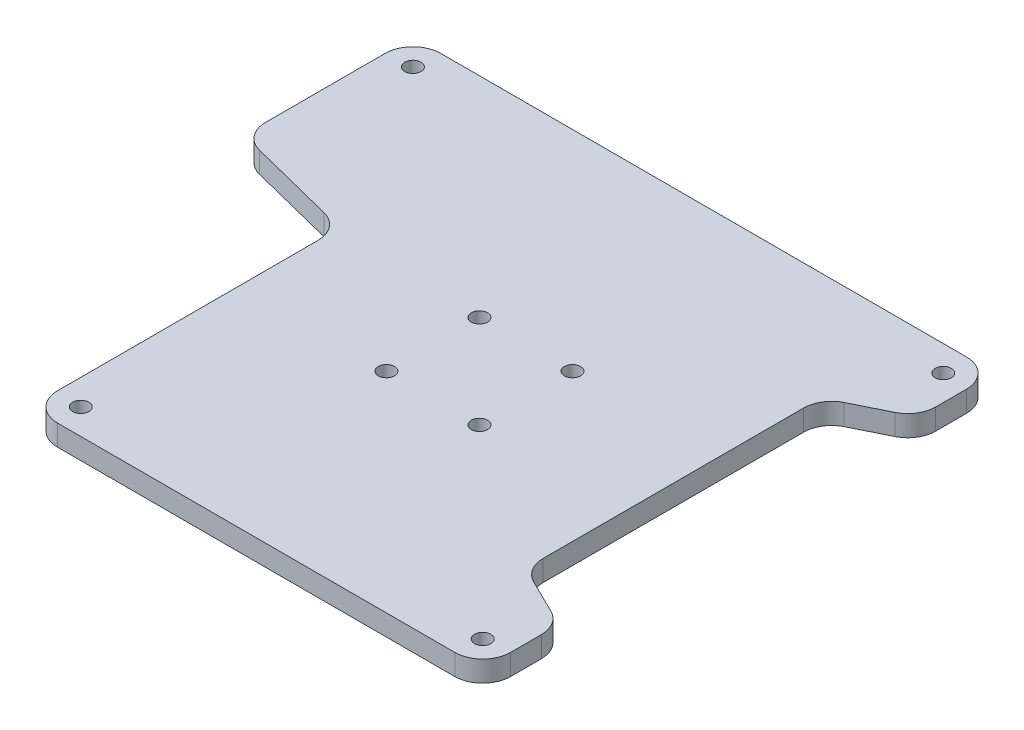
SolidWorks part; units mm, degrees
ref_plane "Front Plane" through (0, 0, 0) normal (0, 0, 1) x (1, 0, 0)
ref_plane "Top Plane" through (0, 0, 0) normal (0, 1, 0) x (1, 0, 0)
ref_plane "Right Plane" through (0, 0, 0) normal (1, 0, 0) x (0, 0, -1)
sketch "Sketch1" plane through (0, 0, 0) normal (0, 1, 0) x (1, 0, 0)
  line L0 (-41.7, 0) -> (41.7, 0) construction
  line L1 (-35.7, -55) -> (49.7, -55)
  line L2 (55.7, -49) -> (55.7, -42.3778)
  line L3 (52.3607, -37) -> (45.0393, -33.3778)
  line L4 (41.7, -28) -> (41.7, 28)
  line L5 (45.0393, 33.3778) -> (52.3607, 37)
  line L6 (55.7, 42.3778) -> (55.7, 49)
  line L7 (49.7, 55) -> (-63.3, 55)
  line L8 (-69.3, 49) -> (-69.3, 23.3173)
  line L9 (-64.7694, 17.5) -> (-46.2306, 12.8173)
  line L10 (-41.7, 7) -> (-41.7, -49)
  line L11 (-36.8, 20.5) -> (23.2, 20.5) construction
  line L12 (34.04, -3.15) -> (35.74, -3.15) construction
  line L13 (34.04, -3.15) -> (34.04, 3.15) construction
  line L14 (34.04, 3.15) -> (35.74, 3.15) construction
  line L15 (35.74, -3.15) -> (35.74, 3.15) construction
  line L16 (34.04, -3.15) -> (35.74, 3.15) construction
  line L17 (34.04, 3.15) -> (35.74, -3.15) construction
  line L18 (-33.5, -3.15) -> (-31.8, -3.15) construction
  line L19 (-33.5, -3.15) -> (-33.5, 3.15) construction
  line L20 (-33.5, 3.15) -> (-31.8, 3.15) construction
  line L21 (-31.8, -3.15) -> (-31.8, 3.15) construction
  line L22 (-33.5, -3.15) -> (-31.8, 3.15) construction
  line L23 (-33.5, 3.15) -> (-31.8, -3.15) construction
  line L24 (23.2, 20.5) -> (41.7, 20.5) construction
  line L25 (-41.7, -20) -> (-6.7, -20) construction
  line L26 (-6.7, -20) -> (-6.7, -55) construction
  line L27 (50.2, 55) -> (50.2, 49.5) construction
  line L28 (50.2, 49.5) -> (55.7, 49.5) construction
  line L29 (-63.8, 55) -> (-63.8, 49.5) construction
  line L30 (-63.8, 49.5) -> (-69.3, 49.5) construction
  line L31 (-41.7, -49.5) -> (-36.2, -49.5) construction
  line L32 (-36.2, -49.5) -> (-36.2, -55) construction
  line L33 (50.2, -55) -> (50.2, -49.5) construction
  line L34 (50.2, -49.5) -> (55.7, -49.5) construction
  line L36 (-10, -10) -> (10, -10) construction
  line L37 (-10, -10) -> (-10, 10) construction
  line L38 (-10, 10) -> (10, 10) construction
  line L39 (10, -10) -> (10, 10) construction
  line L40 (-10, -10) -> (10, 10) construction
  line L41 (-10, 10) -> (10, -10) construction
  arc A0 (49.7, -55) -> (55.7, -49) centre (49.7, -49) ccw
  arc A1 (55.7, -42.3778) -> (52.3607, -37) centre (49.7, -42.3778) ccw
  arc A2 (45.0393, -33.3778) -> (41.7, -28) centre (47.7, -28) cw
  arc A3 (41.7, 28) -> (45.0393, 33.3778) centre (47.7, 28) cw
  arc A4 (52.3607, 37) -> (55.7, 42.3778) centre (49.7, 42.3778) ccw
  arc A5 (55.7, 49) -> (49.7, 55) centre (49.7, 49) ccw
  arc A6 (-63.3, 55) -> (-69.3, 49) centre (-63.3, 49) ccw
  arc A7 (-69.3, 23.3173) -> (-64.7694, 17.5) centre (-63.3, 23.3173) ccw
  arc A8 (-46.2306, 12.8173) -> (-41.7, 7) centre (-47.7, 7) cw
  arc A9 (-41.7, -49) -> (-35.7, -55) centre (-35.7, -49) ccw
  circle A10 centre (-63.8, 49.5) radius 1.75
  circle A11 centre (50.2, 49.5) radius 1.5 construction
  circle A12 centre (-36.2, -49.5) radius 1.75
  circle A13 centre (50.2, -49.5) radius 1.75
  circle A14 centre (-36.8, 20.5) radius 2.75 construction
  circle A15 centre (23.2, 20.5) radius 2.5 construction
  circle A16 centre (-6.7, -20) radius 2.75 construction
  circle A17 centre (23.2, 20.5) radius 2.75 construction
  circle A18 centre (50.2, 49.5) radius 1.75
  circle A19 centre (10, 10) radius 1.5 construction
  circle A20 centre (-10, 10) radius 1.75
  circle A21 centre (-10, -10) radius 1.75
  circle A22 centre (10, -10) radius 1.75
  circle A23 centre (10, 10) radius 1.75
  point P2 (0, 0)
  point P37 (41.7, 0)
  point P49 (34.89, 0)
  point P54 (-32.65, 0)
  point P74 (0, 0)
  dimension "D4" = 6
  dimension "D15" = 5
  dimension "D21" = 3
  dimension "D24" = 3
  dimension "D1" = 110
  dimension "D2" = 125
  dimension "D3" = 18
  dimension "D5" = 27
  dimension "D6" = 83.4
  dimension "D7" = 27.6
  dimension "D8" = 37.5
  dimension "D9" = 48
  dimension "D10" = 6.3
  dimension "D11" = 1.7
  dimension "D12" = 8.2
  dimension "D13" = 65.84
  dimension "D16" = 18.5
  dimension "D17" = 60
  dimension "D18" = 34.5
  dimension "D19" = 35
  dimension "D22" = 5.5
  dimension "D25" = 20
  dimension "D14" = 0.25
  dimension "D20" = 0.25
  dimension "D23" = 0.25
extrude "Boss-Extrude1" add sketch "Sketch1" along normal blind 4.5
equation "\"Tolerance\"=0.25"
equation "\"D14@Sketch1\"=\"Tolerance\""
equation "\"D20@Sketch1\"=\"Tolerance\""
equation "\"D23@Sketch1\"=\"Tolerance\""
